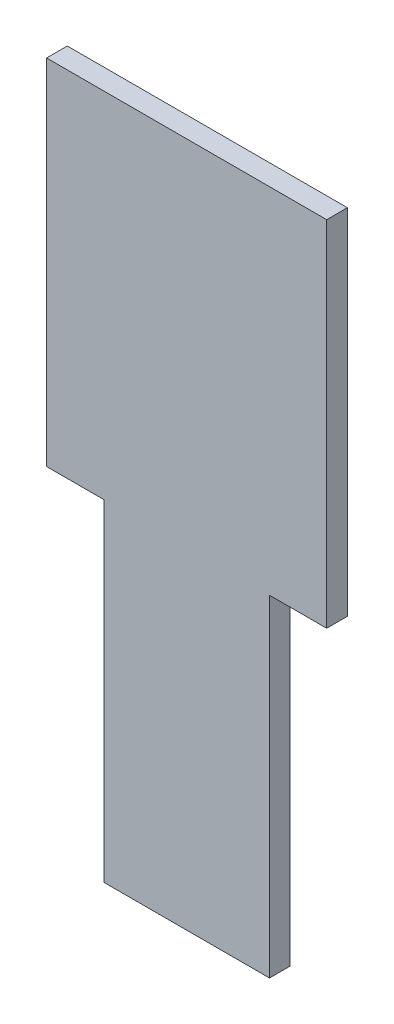
SolidWorks part; units mm, degrees
material "6061 Alloy"
ref_plane "Front Plane" through (0, 0, 0) normal (0, 0, 1) x (1, 0, 0)
ref_plane "Top Plane" through (0, 0, 0) normal (0, 1, 0) x (1, 0, 0)
ref_plane "Right Plane" through (0, 0, 0) normal (1, 0, 0) x (0, 0, -1)
sketch "Sketch1" plane through (0, 0, 0) normal (0, 0, 1) x (1, 0, 0)
  line L1 (-42.926, 105.029) -> (42.926, 105.029)
  line L2 (-42.926, 105.029) -> (-42.926, -105.029)
  line L3 (-42.926, -105.029) -> (42.926, -105.029)
  line L4 (42.926, 105.029) -> (42.926, -105.029)
  line L5 (-42.926, 105.029) -> (42.926, -105.029) construction
  line L6 (-42.926, -105.029) -> (42.926, 105.029) construction
  point P0 (0, 0)
  dimension "D1" = 210.058
  dimension "D2" = 85.852
extrude "Boss-Extrude1" add sketch "Sketch1" along normal blind 6.35
sketch "Sketch2" plane through (0, 0, 6.35) normal (0, 0, 1) x (1, 0, 0)
  line L0 (42.926, -3.429) -> (25.4, -3.429)
  line L1 (42.926, -105.029) -> (42.926, 105.029) construction
  line L2 (42.926, -105.029) -> (25.4, -105.029)
  line L3 (25.4, -105.029) -> (25.4, -3.429)
  line L4 (42.926, -105.029) -> (42.926, -3.429)
  line L5 (-42.926, -3.429) -> (-25.273, -3.429)
  line L6 (-42.926, 105.029) -> (-42.926, -105.029) construction
  line L7 (-25.273, -3.429) -> (-25.273, -105.029)
  line L8 (-42.926, -105.029) -> (42.926, -105.029) construction
  line L9 (-25.273, -105.029) -> (-42.926, -105.029)
  line L10 (-42.926, -105.029) -> (-42.926, -3.429)
  dimension "D1" = 17.526
  dimension "D2" = 101.6
extrude "Cut-Extrude1" cut sketch "Sketch2" against normal up to next
